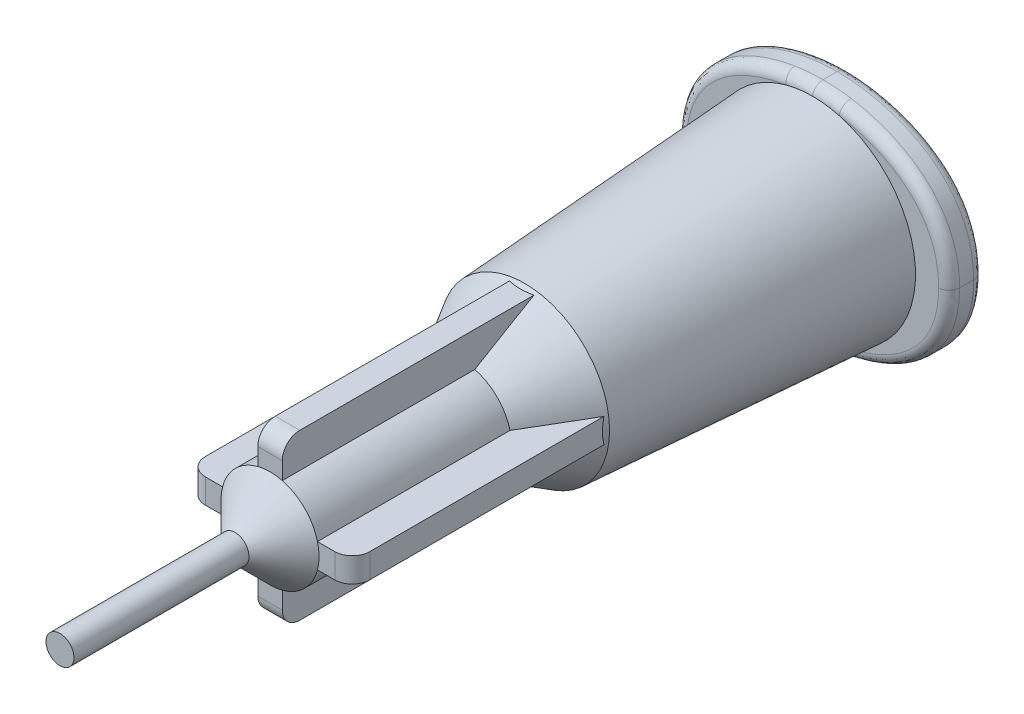
SolidWorks part; units mm, degrees
ref_plane "Front Plane" through (0, 0, 0) normal (0, 0, 1) x (1, 0, 0)
ref_plane "Top Plane" through (0, 0, 0) normal (0, 1, 0) x (1, 0, 0)
ref_plane "Right Plane" through (0, 0, 0) normal (1, 0, 0) x (0, 0, -1)
sketch "Sketch1" plane through (0, 0, 0) normal (0, 1, 0) x (1, 0, 0)
  line L0 (0, -8) -> (0, 0) construction
  line L1 (0, 0) -> (2.5, 0) construction
  line L2 (2.5, 0) -> (3, 0)
  line L3 (3, 0) -> (3.9, 0)
  line L4 (2.4244, -9.2257) -> (1.4, -11)
  line L5 (1.4, -11) -> (1.4, -16.5)
  line L6 (1.4, -16.5) -> (0.4, -16.5)
  line L7 (0, -16.5) -> (0, -8) construction
  line L8 (2, -8) -> (0.4, -8)
  line L9 (2, -8) -> (2.5, 0)
  line L10 (3.9, 0) -> (3.9, -1)
  line L11 (3.9, -1) -> (2.9385, -1)
  line L12 (2.9385, -1) -> (2.4244, -9.2257)
  line L13 (0.4, -16.5) -> (0.4, -8)
  point P20 (3.45, 0)
  dimension "D1" = 3
  dimension "D2" = 2.5
  dimension "D3" = 0.4
  dimension "D4" = 5.5
  dimension "D5" = 1.4
  dimension "D6" = 2
  dimension "D7" = 150
  dimension "D8" = 8
  dimension "D9" = 3.9
  dimension "D10" = 1
  dimension "D11" = 0.5
  dimension "D12" = 16.5
revolve "Revolve1" add sketch "Sketch1" angle 360 about L7
sketch "Sketch2" plane through (0, 0, 0) normal (0, 1, 0) x (1, 0, 0)
  line L0 (-1.4, -16.5) -> (1.4, -16.5) construction
  line L1 (1.8414, -16.5) -> (1.4, -16.5) construction
  line L2 (2.35, -9.0947) -> (1.25, -11)
  line L3 (1.4, -11) -> (-1.4, -11) construction
  line L5 (0, 0) -> (0, -15) construction
  line L7 (1.25, -11) -> (1.25, -16.5)
  line L8 (1.25, -16.5) -> (2.35, -16.5)
  line L9 (1.4, -11) -> (2.4244, -9.2257) construction
  line L10 (2.35, -16.5) -> (2.35, -9.0947)
  dimension "D1" = 2.35
  dimension "D2" = 0.15
extrude "Boss-Extrude1" add sketch "Sketch2" along normal mid plane 0.7
pattern_circular "CirPattern1" count 4 over 360 about axis through (0, 0, 0) along (0, 0, 1) of "Boss-Extrude1"
sketch "Sketch4" plane through (0, 0, 0) normal (0, 0, -1) x (-1, 0, 0)
  line L0 (0, 0) -> (0, 3.9) construction
  line L1 (0, 0) -> (-3.9, 0) construction
  line L2 (0, 3.2) -> (-1.4638, 3.2) construction
  circle A0 centre (0, 0) radius 3.9 construction
  circle A1 centre (0, 0) radius 5.5
  spline S0 degree 3 poles (0, 3.2) (-1.6816, 3.2) (-3.9, 2.3226) (-3.9, 0) knots 0 0 0 0 1 1 1 1
  spline S1 degree 3 poles (0, 3.2) (1.6816, 3.2) (3.9, 2.3226) (3.9, 0) knots 0 0 0 0 1 1 1 1
  spline S2 degree 3 poles (0, -3.2) (-1.6816, -3.2) (-3.9, -2.3226) (-3.9, 0) knots 0 0 0 0 1 1 1 1
  spline S3 degree 3 poles (0, -3.2) (1.6816, -3.2) (3.9, -2.3226) (3.9, 0) knots 0 0 0 0 1 1 1 1
  dimension "D1" = 0.7
  dimension "D2" = 11
extrude "Cut-Extrude2" cut sketch "Sketch4" against normal through all
fillet "Fillet1" radius 0.3 8 edges
sketch "Sketch5" plane through (0, 0, 0) normal (0, 1, 0) x (1, 0, 0)
  line L0 (0, 0) -> (0, -17.5) construction
  line L1 (0, -16.5) -> (1.4, -16.5)
  line L2 (-0.35, -16.5) -> (0.35, -16.5) construction
  line L3 (0, -17.5) -> (0.4, -17.5)
  line L4 (0, -17.5) -> (0, -16.5)
  line L5 (0.4, -17.5) -> (1.4, -16.5)
  dimension "D1" = 45
  dimension "D2" = 1.4
  dimension "D3" = 0.4
revolve "Revolve2" add sketch "Sketch5" angle 360 about L0
sketch "Sketch6" plane through (0, 0, 0) normal (0, 1, 0) x (1, 0, 0)
  line L0 (0, -17.5) -> (0.4, -17.5)
  line L1 (-0.4, -17.5) -> (0.4, -17.5) construction
  line L2 (0.4, -17.5) -> (0.4, -22.5)
  line L3 (0.4, -22.5) -> (0, -22.5)
  line L4 (0, -22.5) -> (0, -17.5)
  dimension "D1" = 5
revolve "Revolve3" add sketch "Sketch6" angle 360 about L4
fillet "Fillet2" radius 0.5 4 edges at (2.35, 0, 16.5) (0, 2.35, 16.5) (-2.35, 0, 16.5) (0, -2.35, 16.5)
